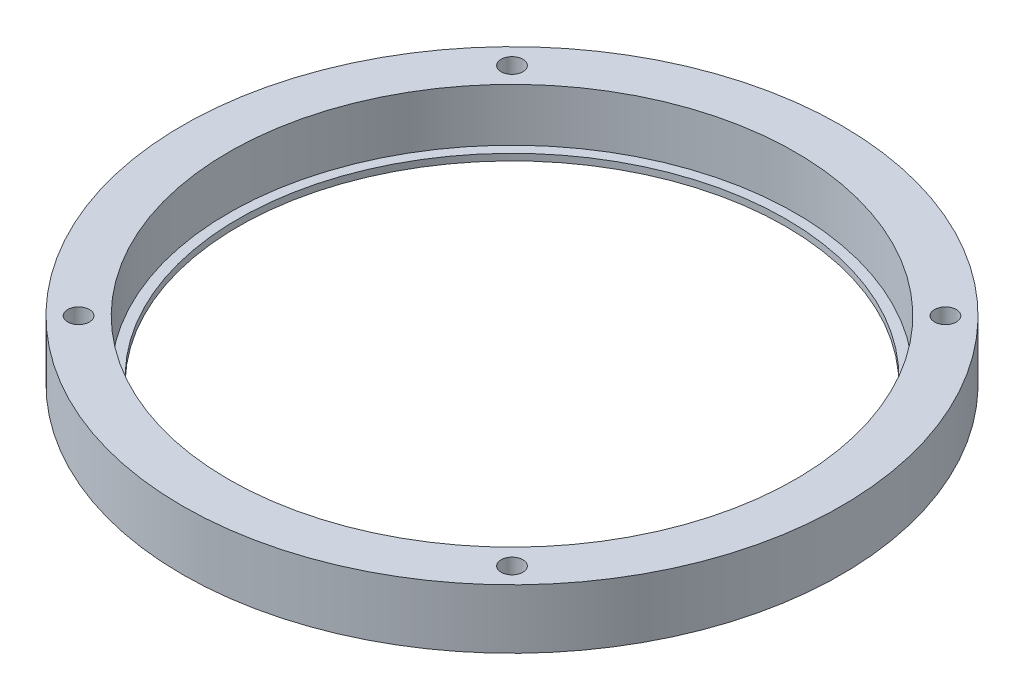
SolidWorks part; units mm, degrees
material "6061 合金"
ref_plane "前视基准面" through (0, 0, 0) normal (0, 0, 1) x (1, 0, 0)
ref_plane "上视基准面" through (0, 0, 0) normal (0, 1, 0) x (1, 0, 0)
ref_plane "右视基准面" through (0, 0, 0) normal (1, 0, 0) x (0, 0, -1)
sketch "草图2" plane through (0, 0, 0) normal (0, 1, 0) x (1, 0, 0)
  circle A0 centre (0, 0) radius 50
  circle A1 centre (0, 0) radius 43
  dimension "D1" = 100
  dimension "D2" = 86
extrude "凸台-拉伸1" add sketch "草图2" along normal blind 8
sketch "草图3" plane through (0, 0, 0) normal (0, -1, 0) x (1, 0, 0)
  circle A0 centre (0, 0) radius 41.5
  circle A1 centre (0, 0) radius 50
  circle A2 centre (0, 0) radius 50
  dimension "D2" = 83
  dimension "D1" = 0
extrude "凸台-拉伸2" add sketch "草图3" along normal blind 1
hole_wizard "M4 螺纹孔1" positions "草图4" profile "草图5" tap size "M4" standard "GB" end condition through all
sketch "草图4" plane through (0, 8, 0) normal (0, 1, 0) x (1, 0, 0)
  line L1 (-32.8805, 32.8805) -> (32.8805, 32.8805) construction
  line L2 (-32.8805, 32.8805) -> (-32.8805, -32.8805) construction
  line L3 (-32.8805, -32.8805) -> (32.8805, -32.8805) construction
  line L4 (32.8805, 32.8805) -> (32.8805, -32.8805) construction
  circle A0 centre (0, 0) radius 46.5 construction
  point P0 (-32.8805, 32.8805)
  point P2 (-32.8805, -32.8805)
  point P4 (32.8805, -32.8805)
  point P6 (32.8805, 32.8805)
  dimension "D1" = 93
cosmetic thread "孔螺蚊线1"
cosmetic thread "孔螺蚊线2"
cosmetic thread "孔螺蚊线3"
cosmetic thread "孔螺蚊线4"
sketch "草图5" plane through (-32.8805, 8, -32.8805) normal (1, 0, 0) x (0, 0, 1)
  line L0 (0, 0) -> (0, 9)
  line L1 (0, 9) -> (1.65, 9)
  line L2 (1.65, 9) -> (1.65, 0)
  line L5 (1.65, 0) -> (0, 0)
  line L11 (0, -6.35) -> (0, 107.95) construction
  dimension "通孔螺纹孔钻头直径" = 3.3
  dimension "通孔螺纹孔钻头深度" = 9
